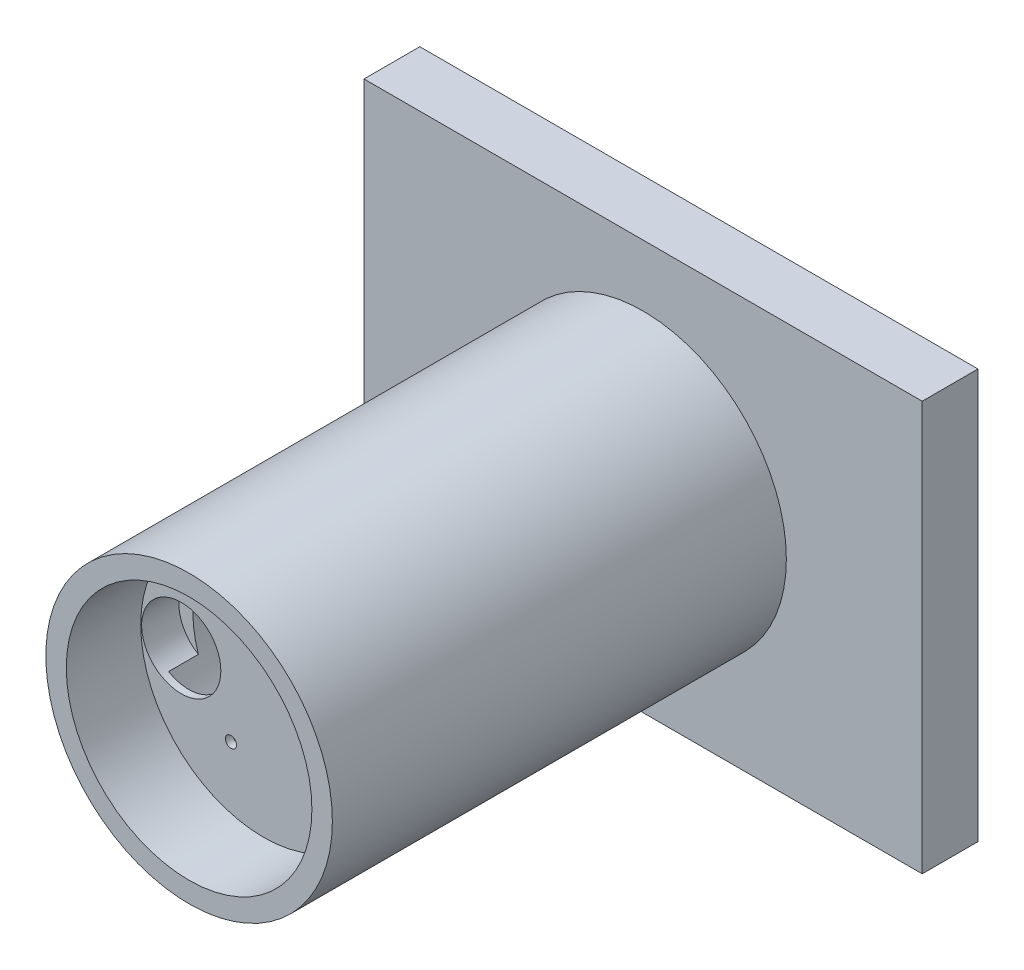
SolidWorks part; units mm, degrees
ref_plane "前视基准面" through (0, 0, 0) normal (0, 0, 1) x (1, 0, 0)
ref_plane "上视基准面" through (0, 0, 0) normal (0, 1, 0) x (1, 0, 0)
ref_plane "右视基准面" through (0, 0, 0) normal (1, 0, 0) x (0, 0, -1)
other "Configuration Table"
sketch "草图1" plane through (0, 0, 0) normal (0, 0, 1) x (1, 0, 0)
  line L1 (-75, -55) -> (75, -55)
  line L2 (-75, -55) -> (-75, 55)
  line L3 (-75, 55) -> (75, 55)
  line L4 (75, -55) -> (75, 55)
  line L5 (-75, -55) -> (75, 55) construction
  line L6 (-75, 55) -> (75, -55) construction
  point P0 (0, 0)
  dimension "D1" = 150
  dimension "D2" = 110
extrude "凸台-拉伸1" add sketch "草图1" along normal blind 15
sketch "草图2" plane through (0, 0, 15) normal (0, 0, 1) x (1, 0, 0)
  circle A0 centre (0, 0) radius 38.5
  dimension "D1" = 77
extrude "凸台-拉伸2" add sketch "草图2" along normal blind 100
sketch "草图4" plane through (0, 0, 115) normal (0, 0, 1) x (1, 0, 0)
  circle A0 centre (0, 0) radius 29
  dimension "D1" = 58
extrude "切除-拉伸1" cut sketch "草图4" against normal blind 145
sketch "草图5" plane through (0, 0, 115) normal (0, 0, 1) x (1, 0, 0)
  circle A0 centre (0, 0) radius 33
  dimension "D1" = 66
extrude "凸台-拉伸3" add sketch "草图5" along normal blind 2
sketch "草图6" plane through (0, 0, 117) normal (0, 0, 1) x (1, 0, 0)
  circle A0 centre (0, 0) radius 17.5 construction
  circle A1 centre (17.5, 0) radius 1.5
  circle A2 centre (-8.75, -15.1554) radius 1.5
  circle A3 centre (-8.75, 15.1554) radius 1.5
  point P11 (0, 0)
  dimension "D1" = 35
  dimension "D2" = 3
  dimension "D3" = 3
extrude "切除-拉伸2" cut sketch "草图6" against normal blind 2
sketch "草图7" plane through (0, 0, 115) normal (0, 0, 1) x (1, 0, 0)
  circle A1 centre (0, 0) radius 38.5
  circle A2 centre (0, 0) radius 38.5
  circle A4 centre (0, 0) radius 33
  circle A5 centre (0, 0) radius 33
  dimension "D1" = 0
  dimension "D2" = 0
extrude "凸台-拉伸4" add sketch "草图7" along normal blind 22
sketch "草图8" plane through (0, 0, 117) normal (0, 0, 1) x (1, 0, 0)
  circle A0 centre (-22.1109, 0) radius 10.643
extrude "切除-拉伸3" cut sketch "草图8" against normal blind 10
